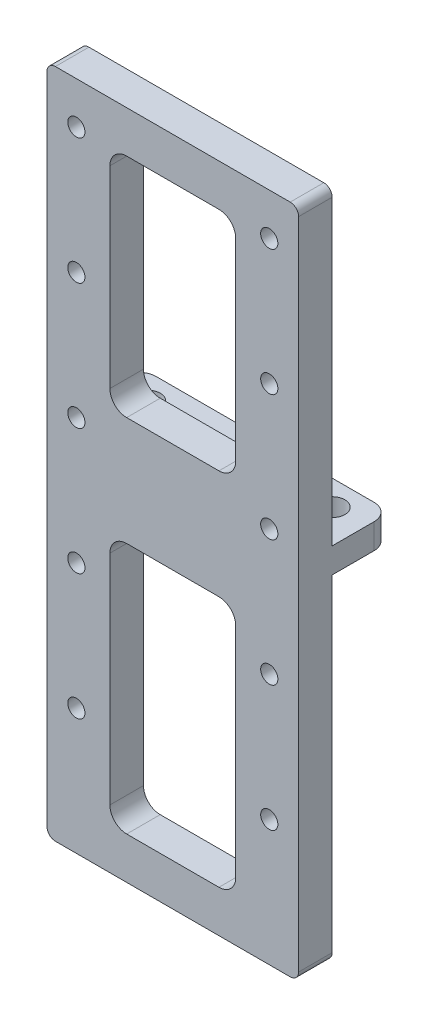
SolidWorks part; units mm, degrees
material "6061 合金"
ref_plane "前视基准面" through (0, 0, 0) normal (0, 0, 1) x (1, 0, 0)
ref_plane "上视基准面" through (0, 0, 0) normal (0, 1, 0) x (1, 0, 0)
ref_plane "右视基准面" through (0, 0, 0) normal (1, 0, 0) x (0, 0, -1)
other "Configuration Table"
sketch "草图1" plane through (0, 0, 0) normal (0, 0, 1) x (1, 0, 0)
  line L1 (-15, -40) -> (15, -40)
  line L2 (-15, -40) -> (-15, 40)
  line L3 (-15, 40) -> (15, 40)
  line L4 (15, -40) -> (15, 40)
  line L5 (-15, -40) -> (15, 40) construction
  line L6 (-15, 40) -> (15, -40) construction
  point P0 (0, 0)
  dimension "D1" = 80
  dimension "D2" = 30
extrude "凸台-拉伸1" add sketch "草图1" along normal blind 4
sketch "草图2" plane through (0, 0, 4) normal (0, 0, 1) x (1, 0, 0)
  circle A0 centre (-11.5, 35) radius 1.2 construction
  circle A1 centre (11.5, 35) radius 1.2 construction
  circle A2 centre (-11.5, 35) radius 1.2 construction
  circle A3 centre (11.5, 35) radius 1.2 construction
  circle A4 centre (11.5, 35) radius 1.025
  circle A5 centre (-11.5, 35) radius 1.025
  dimension "D1" = 2.05
extrude "切除-拉伸1" cut sketch "草图2" against normal blind 10
pattern_linear "阵列(线性)1" count 5 spacing 15 along (0, -1, 0) of "切除-拉伸1"
sketch "草图4" plane through (0, 0, 4) normal (0, 0, -1) x (-1, 0, 0)
  line L0 (-15, -40) -> (-15, 40) construction
  line L1 (-15, 0) -> (15, 0)
  line L2 (-15, 0) -> (-15, 3)
  line L3 (-15, 3) -> (15, 3)
  line L4 (15, 0) -> (15, 3)
  line L6 (15, -40) -> (-15, -40) construction
  line L7 (15, 40) -> (15, -40) construction
  dimension "D1" = 40
  dimension "D2" = 3
extrude "凸台-拉伸2" [suppressed] add sketch "草图4" against normal blind 7
sketch "草图5" plane through (0, 0, 0) normal (0, 0, -1) x (-1, 0, 0)
  line L0 (-15, -40) -> (-15, 40) construction
  line L1 (-15, 0) -> (15, 0)
  line L2 (-15, 0) -> (-15, 3)
  line L3 (-15, 3) -> (15, 3)
  line L4 (15, 0) -> (15, 3)
  line L6 (15, -40) -> (-15, -40) construction
  line L7 (15, 40) -> (15, -40) construction
  dimension "D1" = 40
  dimension "D2" = 3
extrude "凸台-拉伸3" add sketch "草图5" along normal blind 7
fillet "圆角1" radius 1 4 edges at (15, -40, 2) (-15, -40, 2) (15, 40, 2) (-15, 40, 2)
sketch "草图6" plane through (0, 0, 0) normal (0, 0, -1) x (-1, 0, 0)
  line L0 (0, 40) -> (0, 3) construction
  line L1 (-14, 40) -> (14, 40) construction
  line L2 (15, 3) -> (-15, 3) construction
  line L4 (-7.5, 8) -> (7.5, 8)
  line L5 (-7.5, 8) -> (-7.5, 35)
  line L6 (-7.5, 35) -> (7.5, 35)
  line L7 (7.5, 8) -> (7.5, 35)
  line L8 (-7.5, 8) -> (7.5, 35) construction
  line L9 (-7.5, 35) -> (7.5, 8) construction
  circle A0 centre (11.5, 35) radius 1.025 construction
  point P6 (0, 21.5)
  dimension "D1" = 4
  dimension "D2" = 5
extrude "切除-拉伸2" cut sketch "草图6" against normal mid plane 66
fillet "圆角2" radius 2 4 edges at (7.5, 35, 2) (-7.5, 35, 2) (-7.5, 8, 2) (7.5, 8, 2)
sketch "草图7" plane through (0, 0, 0) normal (0, 0, -1) x (-1, 0, 0)
  line L0 (0, 0) -> (0, -40) construction
  line L1 (14, -40) -> (-14, -40) construction
  line L2 (7.5, 10) -> (7.5, 33) construction
  line L3 (-7.5, -35) -> (7.5, -35)
  line L4 (-7.5, -35) -> (-7.5, -5)
  line L5 (-7.5, -5) -> (7.5, -5)
  line L6 (7.5, -35) -> (7.5, -5)
  line L7 (-7.5, -35) -> (7.5, -5) construction
  line L8 (-7.5, -5) -> (7.5, -35) construction
  point P5 (0, -20)
  dimension "D1" = 5
extrude "切除-拉伸3" cut sketch "草图7" against normal mid plane 66
fillet "圆角3" radius 2 4 edges at (7.5, -35, 2) (-7.5, -35, 2) (-7.5, -5, 2) (7.5, -5, 2)
sketch "草图8" [suppressed] plane through (0, 0, 4) normal (0, 0, 1) x (1, 0, 0)
  line L0 (0, 40) -> (0, 3) construction
  line L1 (14, 40) -> (-14, 40) construction
  line L2 (-15, 3) -> (15, 3) construction
  line L3 (0, 0) -> (0, -40) construction
  line L4 (-7.5, 8) -> (7.5, 8)
  line L5 (-7.5, 8) -> (-7.5, 35)
  line L6 (-7.5, 35) -> (7.5, 35)
  line L7 (7.5, 8) -> (7.5, 35)
  line L8 (-7.5, 8) -> (7.5, 35) construction
  line L9 (-7.5, 35) -> (7.5, 8) construction
  line L10 (-14, -40) -> (14, -40) construction
  line L11 (15, 0) -> (-15, 0) construction
  line L12 (-7.5, -35) -> (7.5, -35)
  line L13 (-7.5, -35) -> (-7.5, -5)
  line L14 (-7.5, -5) -> (7.5, -5)
  line L15 (7.5, -35) -> (7.5, -5)
  line L16 (-7.5, -35) -> (7.5, -5) construction
  line L17 (-7.5, -5) -> (7.5, -35) construction
  circle A0 centre (11.5, 35) radius 1.025 construction
  point P6 (0, 21.5)
  point P18 (0, -20)
  dimension "D1" = 5
  dimension "D2" = 4
  dimension "D3" = 5
extrude "切除-拉伸4" [suppressed] cut sketch "草图8" against normal mid plane 66
fillet "圆角4" [suppressed] radius 2
sketch "草图9" [suppressed] plane through (0, 3, 0) normal (0, 1, 0) x (1, 0, 0)
  line L0 (0, -4) -> (0, -11) construction
  line L1 (-15, -4) -> (15, -4) construction
  line L2 (-15, -11) -> (15, -11) construction
  line L3 (-11, -8) -> (11, -8) construction
  circle A0 centre (11, -8) radius 1.525
  circle A1 centre (-11, -8) radius 1.525
  point P9 (0, -7.5)
  point P12 (0, -8)
  dimension "D2" = 3.05
  dimension "D1" = 22
  dimension "D3" = 3
extrude "切除-拉伸5" [suppressed] cut sketch "草图9" against normal mid plane 66
sketch "草图10" plane through (0, 3, 0) normal (0, 1, 0) x (1, 0, 0)
  line L0 (0, 7) -> (0, 0) construction
  line L1 (-15, 7) -> (15, 7) construction
  line L2 (-11, 4) -> (11, 4) construction
  circle A0 centre (11, 4) radius 1.525
  circle A1 centre (-11, 4) radius 1.525
  point P8 (0, 4)
  dimension "D2" = 3.05
  dimension "D1" = 22
  dimension "D3" = 3
extrude "切除-拉伸6" cut sketch "草图10" against normal mid plane 66
fillet "圆角5" radius 2 2 edges at (-15, 1.5, -7) (15, 1.5, -7)
fillet "圆角6" [suppressed] radius 2
